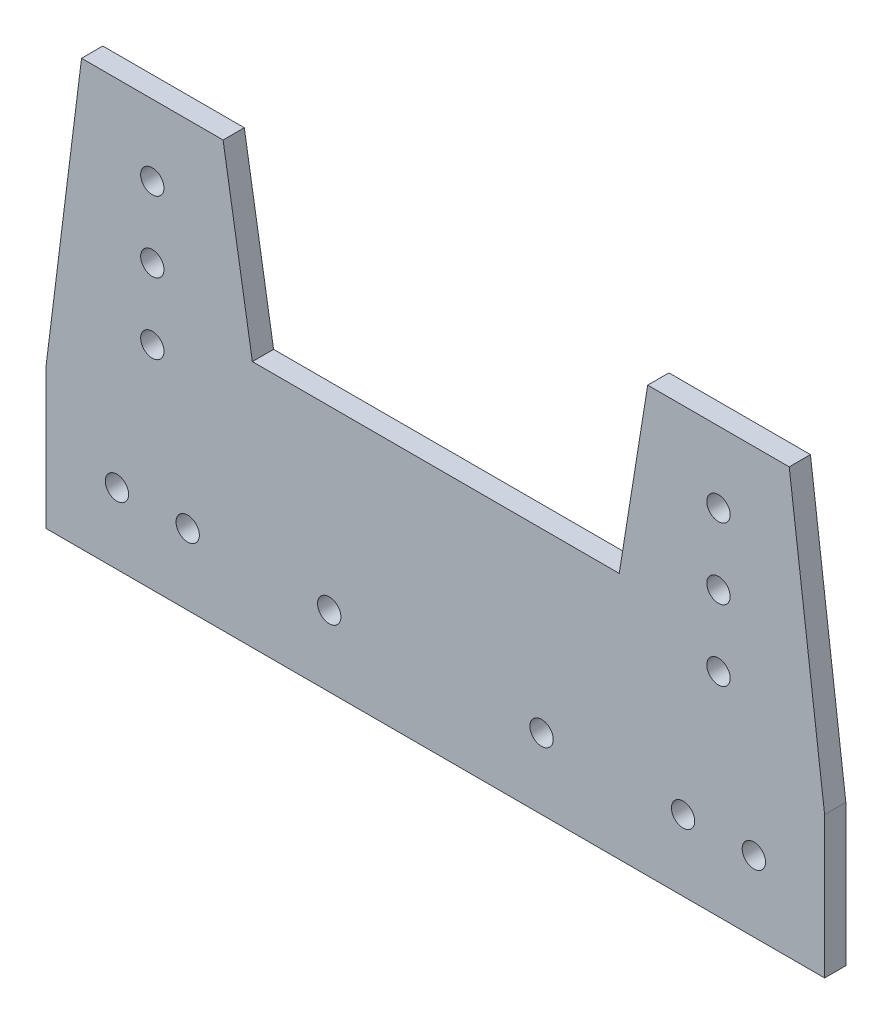
SolidWorks part; units mm, degrees
ref_plane "前视基准面" through (0, 0, 0) normal (0, 0, 1) x (1, 0, 0)
ref_plane "上视基准面" through (0, 0, 0) normal (0, 1, 0) x (1, 0, 0)
ref_plane "右视基准面" through (0, 0, 0) normal (1, 0, 0) x (0, 0, -1)
other "Configuration Table"
sketch "草图1" plane through (0, 0, 0) normal (0, 0, 1) x (1, 0, 0)
  line L7 (-55, 10) -> (-55, -10)
  line L8 (-55, -10) -> (55, -10)
  line L9 (55, 10) -> (55, -10)
  line L10 (-55, 10) -> (55, -10) construction
  line L11 (-55, -10) -> (55, 10) construction
  line L14 (0, 0) -> (0, -10) construction
  line L16 (35, 0) -> (45, 0) construction
  line L18 (-45, 0) -> (-35, 0) construction
  line L19 (0, -10) -> (0, 10) construction
  line L20 (40, 30) -> (40, 40) construction
  line L21 (-25.8642, 25) -> (25.9793, 25)
  line L22 (50, 50.0527) -> (55, 10)
  line L24 (-50, 50.0527) -> (-55, 10)
  line L25 (-50, 50.0527) -> (-30, 50.0527)
  line L26 (-40, 40) -> (-40, 45.2111) construction
  line L27 (-30, 50.0527) -> (-25.8642, 25)
  line L29 (30, 50.0527) -> (25.9793, 25)
  line L30 (30, 50.0527) -> (50, 50.0527)
  circle A2 centre (15, 0) radius 1.65
  circle A3 centre (-15, 0) radius 1.65
  circle A6 centre (35, 0) radius 1.65
  circle A7 centre (-35, 0) radius 1.65
  circle A13 centre (45, 0) radius 1.65
  circle A14 centre (-45, 0) radius 1.65
  circle A15 centre (-40, 20) radius 1.65
  circle A16 centre (-40, 30) radius 1.65
  circle A17 centre (40, 20) radius 1.65
  circle A18 centre (40, 30) radius 1.65
  circle A19 centre (-40, 40) radius 1.65
  circle A20 centre (40, 40) radius 1.65
  point P0 (0, 0)
  point P42 (0, 10)
  dimension "D1" = 20
  dimension "D5" = 3.3
  dimension "D6" = 3.3
  dimension "D7" = 10
  dimension "D14" = 3.3
  dimension "D15" = 3.3
  dimension "D16" = 3.3
  dimension "D10" = 10
  dimension "D11" = 3.3
  dimension "D18" = 3.3
  dimension "D21" = 20
  dimension "D3" = 3.3
  dimension "D4" = 3.3
  dimension "D17" = 3.3
  dimension "D26" = 3.3
  dimension "D29" = 3.3
  dimension "D2" = 110
  dimension "D8" = 15
  dimension "D9" = 15
  dimension "D12" = 20
  dimension "D13" = 20
  dimension "D19" = 20
  dimension "D20" = 10
  dimension "D22" = 10
  dimension "D23" = 35
  dimension "D24" = 10
  dimension "D25" = 20
  dimension "D27" = 10
  dimension "D30" = 100
extrude "凸台-拉伸1" add sketch "草图1" along normal blind 3
